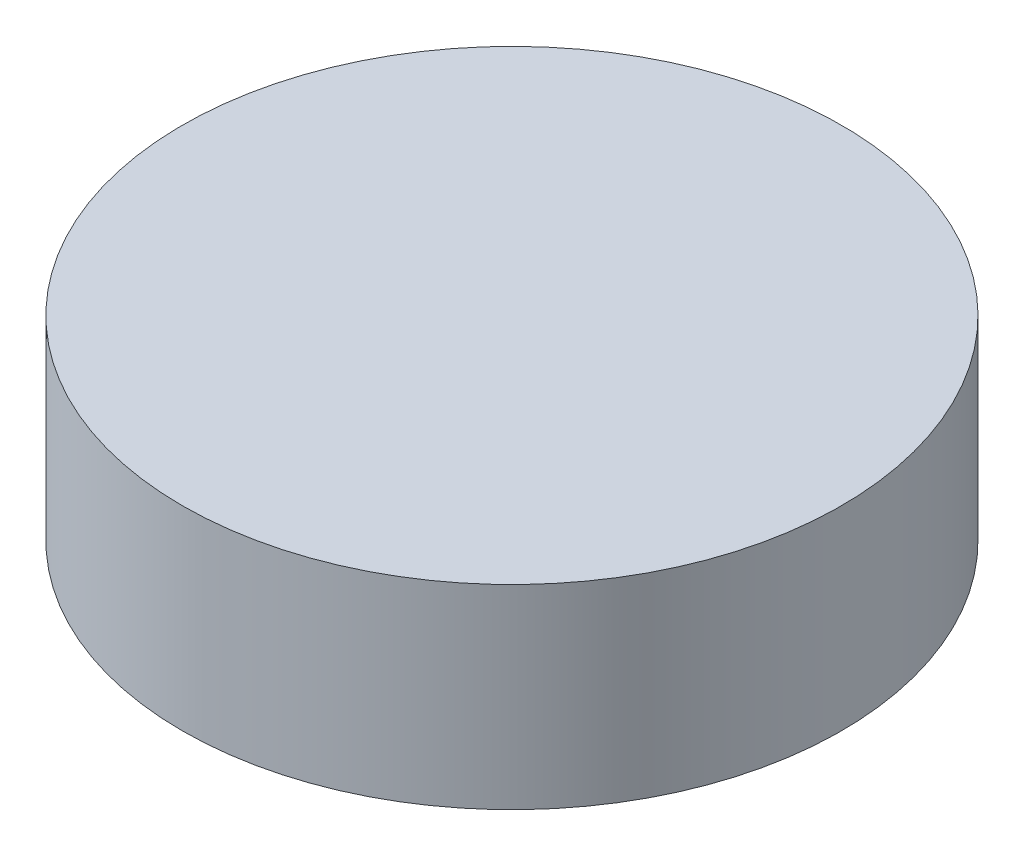
SolidWorks part; units mm, degrees
ref_plane "Front Plane" through (0, 0, 0) normal (0, 0, 1) x (1, 0, 0)
ref_plane "Top Plane" through (0, 0, 0) normal (0, 1, 0) x (1, 0, 0)
ref_plane "Right Plane" through (0, 0, 0) normal (1, 0, 0) x (0, 0, -1)
sketch "Sketch1" plane through (0, 0, 0) normal (0, 1, 0) x (1, 0, 0)
  circle A0 centre (0, 0) radius 2400
  dimension "D1" = 4800
extrude "Boss-Extrude1" add sketch "Sketch1" along normal blind 1420
